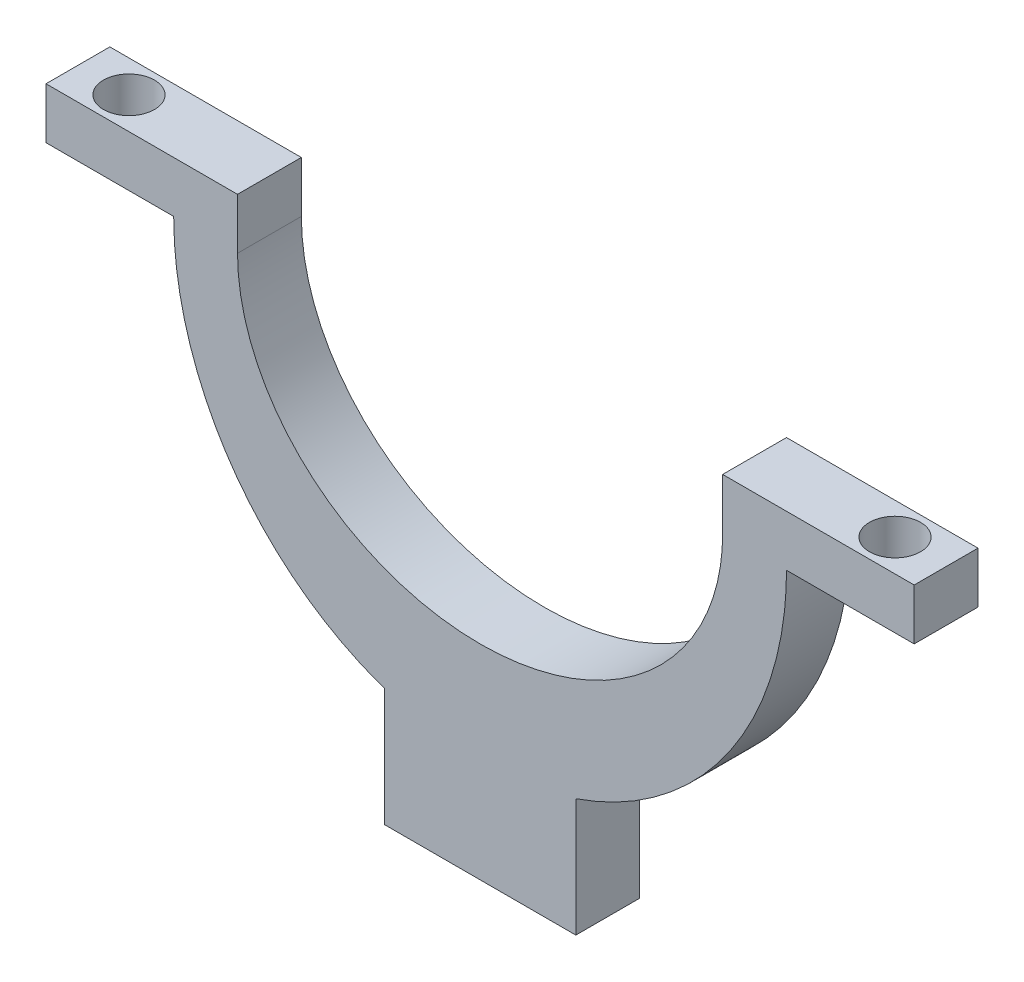
SolidWorks part; units mm, degrees
ref_plane "Front Plane" through (0, 0, 0) normal (0, 0, 1) x (1, 0, 0)
ref_plane "Top Plane" through (0, 0, 0) normal (0, 1, 0) x (1, 0, 0)
ref_plane "Right Plane" through (0, 0, 0) normal (1, 0, 0) x (0, 0, -1)
sketch "Sketch2" plane through (0, 0, 0) normal (0, 0, 1) x (1, 0, 0)
  line L0 (-24, 0) -> (24, 0)
  ellipse E0 centre (0, 0) end of major axis (-19, 0) minor radius 17
  ellipse E1 centre (0, 0) end of major axis (0, -25) minor radius 24
  dimension "D1" = 34
  dimension "D2" = 38
  dimension "D3" = 50
  dimension "D4" = 48
extrude "Boss-Extrude1" add sketch "Sketch2" along normal blind 5 contours L0 E1 E0
sketch "Sketch3" plane through (0, 0, 0) normal (0, 1, 0) x (1, 0, 0)
  line L0 (0, 0) -> (0, -5) construction
  line L1 (-19, 0) -> (-34, 0)
  line L2 (-19, 0) -> (-19, -5)
  line L3 (-19, -5) -> (-34, -5)
  line L4 (-34, 0) -> (-34, -5)
  line L5 (-19, -5) -> (19, -5) construction
  line L6 (19, -5) -> (34, -5)
  line L7 (34, 0) -> (34, -5)
  line L8 (19, 0) -> (34, 0)
  line L9 (19, 0) -> (19, -5)
  point P14 (19, -5)
  dimension "D1" = 15
extrude "Boss-Extrude2" add sketch "Sketch3" along normal blind 4
sketch "Sketch4" plane through (0, 4, 0) normal (0, 1, 0) x (1, 0, 0)
  line L0 (-34, -5) -> (-19, -5) construction
  line L1 (-34, 0) -> (-34, -5) construction
  line L2 (0, 0) -> (0, -5) construction
  line L3 (-19, -5) -> (19, -5) construction
  circle A0 centre (-30, -2.5) radius 2
  circle A1 centre (30, -2.5) radius 2
  dimension "D1" = 4
  dimension "D2" = 2.5
  dimension "D3" = 4
extrude "Cut-Extrude1" cut sketch "Sketch4" against normal through all
ref_plane "Plane1" through (0, -23, 0) normal (0, 1, 0) x (1, 0, 0)
sketch "Sketch5" plane through (0, -23, 0) normal (0, 1, 0) x (1, 0, 0)
  line L0 (-19, -5) -> (19, -5) construction
  line L1 (-7.5, 0) -> (7.5, 0)
  line L2 (-7.5, 0) -> (-7.5, -5)
  line L3 (-7.5, -5) -> (7.5, -5)
  line L4 (7.5, 0) -> (7.5, -5)
  line L5 (-7.5, 0) -> (7.5, -5) construction
  line L6 (-7.5, -5) -> (7.5, 0) construction
  line L7 (19, 0) -> (-19, 0) construction
  line L8 (0, 0) -> (0, -2.5) construction
  point P0 (0, 0)
  dimension "D1" = 15
extrude "Boss-Extrude3" add sketch "Sketch5" against normal blind 10
